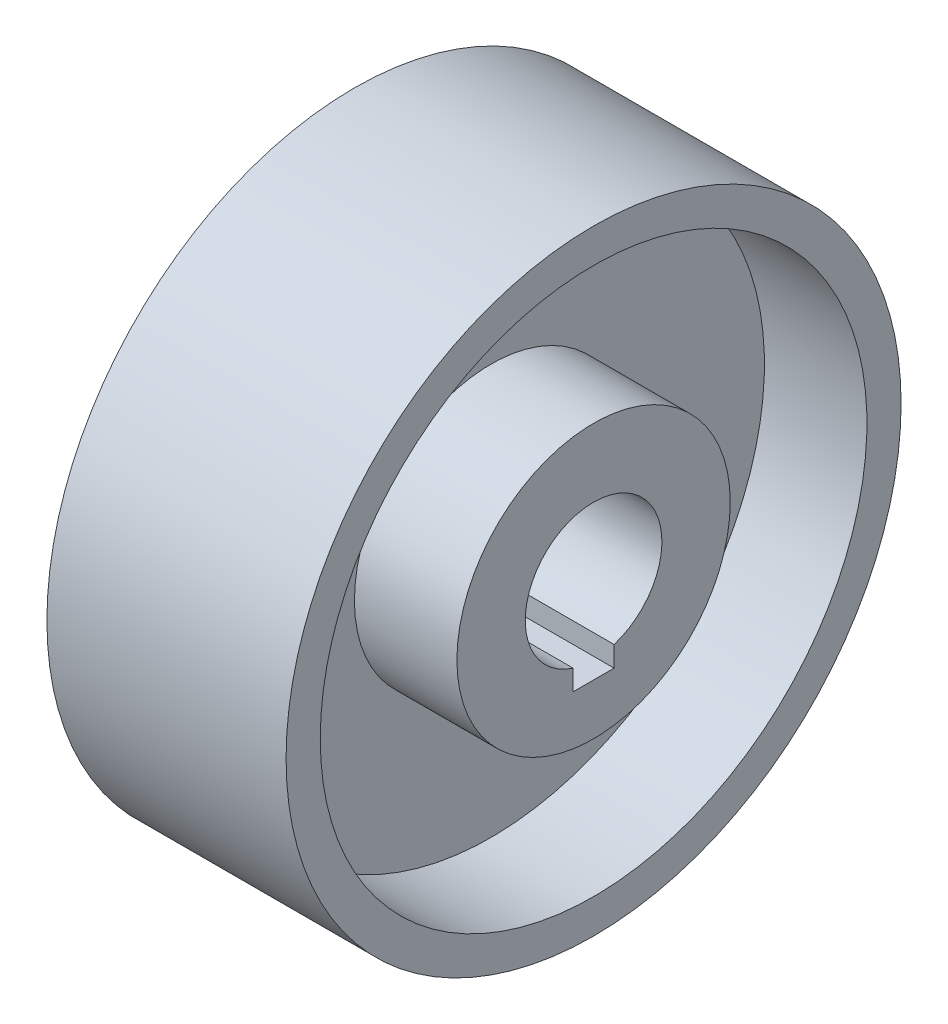
SolidWorks part; units mm, degrees
ref_plane "Front Plane" through (0, 0, 0) normal (0, 0, 1) x (1, 0, 0)
ref_plane "Top Plane" through (0, 0, 0) normal (0, 1, 0) x (1, 0, 0)
ref_plane "Right Plane" through (0, 0, 0) normal (1, 0, 0) x (0, 0, -1)
sketch "Sketch1" plane through (0, 0, 0) normal (0, 1, 0) x (1, 0, 0)
  line L0 (-42.0698, 0) -> (53.2332, 0) construction
  line L1 (-17.5, 45) -> (17.5, 45)
  line L2 (-17.5, 45) -> (-17.5, 40)
  line L4 (17.5, 45) -> (17.5, 40)
  line L5 (-17.5, 20) -> (-17.5, 10)
  line L6 (17.5, 20) -> (17.5, 10)
  line L7 (-17.5, 10) -> (17.5, 10)
  line L9 (-17.5, 40) -> (-2.5, 40)
  line L10 (-2.5, 40) -> (-2.5, 20)
  line L11 (-2.5, 20) -> (-17.5, 20)
  line L12 (17.5, 40) -> (2.5, 40)
  line L13 (2.5, 40) -> (2.5, 20)
  line L14 (2.5, 20) -> (17.5, 20)
  point P0 (0, 0)
  dimension "D3" = 10
  dimension "D5" = 15
  dimension "D6" = 5
  dimension "D7" = 20
  dimension "D8" = 20
  dimension "D14" = 40
revolve "Revolve1" add sketch "Sketch1" angle 360 about L0
sketch "Sketch2" plane through (17.5, 0, 0) normal (1, 0, 0) x (0, 0, -1)
  line L0 (-3, -9.5394) -> (-3, -12.5394)
  line L1 (-3, -12.5394) -> (3, -12.5394)
  line L2 (3, -12.5394) -> (3, -9.5394)
  circle A0 centre (0, 0) radius 10 construction
  arc A1 (-3, -9.5394) -> (3, -9.5394) centre (0, 0) ccw
  point P4 (-3, -11.0394)
  dimension "D1" = 6
  dimension "D2" = 3
  dimension "D3" = 3
extrude "Cut-Extrude1" cut sketch "Sketch2" against normal up to next
